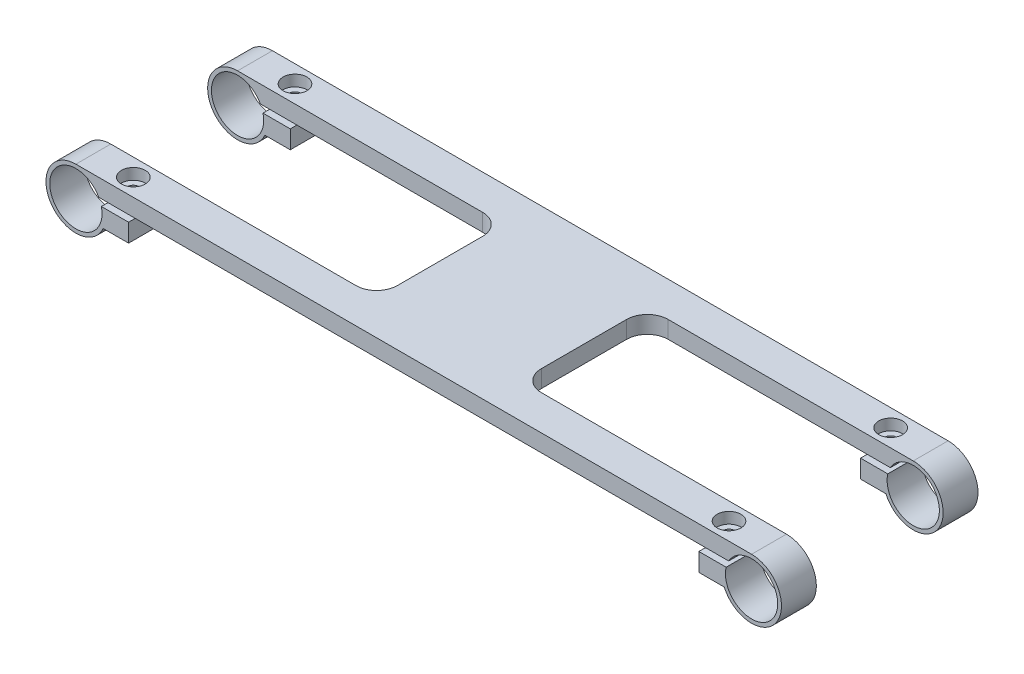
SolidWorks part; units mm, degrees
ref_plane "Front Plane" through (0, 0, 0) normal (0, 0, 1) x (1, 0, 0)
ref_plane "Top Plane" through (0, 0, 0) normal (0, 1, 0) x (1, 0, 0)
ref_plane "Right Plane" through (0, 0, 0) normal (1, 0, 0) x (0, 0, -1)
sketch "Sketch1" plane through (0, 0, 0) normal (0, 0, 1) x (1, 0, 0)
  line L0 (-77.4992, 0) -> (77.4992, 0)
  line L1 (-72.2506, -3.9624) -> (72.2506, -3.9624)
  line L2 (71.5048, -6.858) -> (71.5048, -21.5942) construction
  line L3 (-77.4992, -3.9624) -> (77.4992, -3.9624) construction
  line L4 (-71.5048, -6.858) -> (-71.5048, -16.3097) construction
  line L5 (-65.4088, -5.4864) -> (-65.4088, -9.652)
  line L6 (65.4088, -5.4864) -> (65.4088, -9.652)
  line L7 (65.4088, -6.858) -> (65.4088, -21.5942) construction
  line L8 (-65.4088, -6.858) -> (-65.4088, -16.3097) construction
  line L9 (-71.2362, -9.652) -> (-65.4088, -9.652)
  line L10 (65.4088, -9.652) -> (71.2362, -9.652)
  line L11 (-71.6638, -5.4864) -> (-65.4088, -5.4864)
  line L12 (-77.4992, -9.652) -> (77.4992, -9.652) construction
  line L13 (65.4088, -5.4864) -> (71.6638, -5.4864)
  line L15 (-72.2506, -5.4864) -> (72.2506, -5.4864) construction
  arc A0 (71.6638, -5.4864) -> (72.2506, -3.9624) centre (77.4992, -6.858) ccw
  arc A1 (-72.2506, -3.9624) -> (-71.6638, -5.4864) centre (-77.4992, -6.858) ccw
  arc A2 (-77.4992, 0) -> (-71.2362, -9.652) centre (-77.4992, -6.858) ccw
  arc A3 (71.2362, -9.652) -> (77.4992, 0) centre (77.4992, -6.858) ccw
  dimension "D1" = 11.9888
  dimension "D4" = 13.716
  dimension "D2" = 154.9984
  dimension "D3" = 77.4992
  dimension "D5" = 6.858
  dimension "D6" = 3.9624
  dimension "D7" = 6.096
  dimension "D8" = 6.096
  dimension "D9" = 9.652
  dimension "D10" = 1.524
extrude "Boss-Extrude1" add sketch "Sketch1" along normal mid plane 45.085
sketch "Sketch2" plane through (0, 0, 0) normal (0, 1, 0) x (1, 0, 0)
  line L0 (0, 33.8824) -> (0, -32.7448) construction
  line L1 (-97.5032, 0) -> (111.6412, 0) construction
  line L2 (84.3572, -22.5425) -> (84.3572, 22.5425) construction
  line L3 (84.3572, -14.5415) -> (84.3572, 14.5415)
  line L4 (-84.3572, 22.5425) -> (-84.3572, -22.5425) construction
  line L5 (-84.3572, 14.5415) -> (-84.3572, -14.5415)
  line L6 (-16.51, 9.779) -> (-16.51, -9.779)
  line L7 (16.51, 9.779) -> (16.51, -9.779)
  line L8 (-84.3572, -14.5415) -> (-21.2725, -14.5415)
  line L9 (-84.3572, 14.5415) -> (-21.2725, 14.5415)
  line L10 (-97.5032, 14.5415) -> (111.6412, 14.5415) construction
  line L11 (-97.5032, -14.5415) -> (111.6412, -14.5415) construction
  line L12 (21.2725, 14.5415) -> (84.3572, 14.5415)
  line L13 (21.2725, -14.5415) -> (84.3572, -14.5415)
  line L15 (16.51, 33.8824) -> (16.51, -32.7448) construction
  line L16 (-16.51, 33.8824) -> (-16.51, -32.7448) construction
  arc A0 (21.2725, 14.5415) -> (16.51, 9.779) centre (21.2725, 9.779) ccw
  arc A1 (21.2725, -14.5415) -> (16.51, -9.779) centre (21.2725, -9.779) cw
  arc A2 (-21.2725, -14.5415) -> (-16.51, -9.779) centre (-21.2725, -9.779) ccw
  arc A3 (-16.51, 9.779) -> (-21.2725, 14.5415) centre (-21.2725, 9.779) ccw
  dimension "D5" = 4.7625
  dimension "D1" = 16.51
  dimension "D2" = 16.51
  dimension "D3" = 14.5415
  dimension "D4" = 14.5415
extrude "Cut-Extrude1" cut sketch "Sketch2" against normal blind 14.605
sketch "Sketch3" plane through (0, -9.652, 0) normal (0, -1, 0) x (1, 0, 0)
  line L0 (0, 42.0238) -> (0, -43.0264) construction
  line L1 (69.4077, 0) -> (-38.7722, 0) construction
  line L2 (65.4088, 22.5425) -> (71.2362, 22.5425) construction
  line L3 (65.4088, 22.5425) -> (71.2362, 22.5425) construction
  line L4 (65.4088, 14.5415) -> (71.2362, 14.5415) construction
  line L5 (65.4088, 14.5415) -> (71.2362, 14.5415) construction
  line L6 (68.3225, 22.5425) -> (68.3225, 14.5415) construction
  circle A0 centre (68.3225, 18.542) radius 1.3462
  circle A1 centre (68.3225, -18.542) radius 1.3462
  circle A2 centre (-68.3225, -18.542) radius 1.3462
  circle A3 centre (-68.3225, 18.542) radius 1.3462
  dimension "D1" = 2.6924
extrude "Cut-Extrude2" cut sketch "Sketch3" against normal mid plane 22.225
sketch "Sketch4" plane through (0, 0, 0) normal (0, 1, 0) x (1, 0, 0)
  circle A0 centre (-68.3225, 18.542) radius 2.7305
  circle A1 centre (-68.3225, -18.542) radius 2.7305
  circle A2 centre (68.3225, -18.542) radius 2.7305
  circle A3 centre (68.3225, 18.542) radius 2.7305
  dimension "D1" = 5.461
extrude "Cut-Extrude3" cut sketch "Sketch4" against normal blind 2.54
scale "Scale1" scale about centroid uniform scaling yes scale factor 0.6
